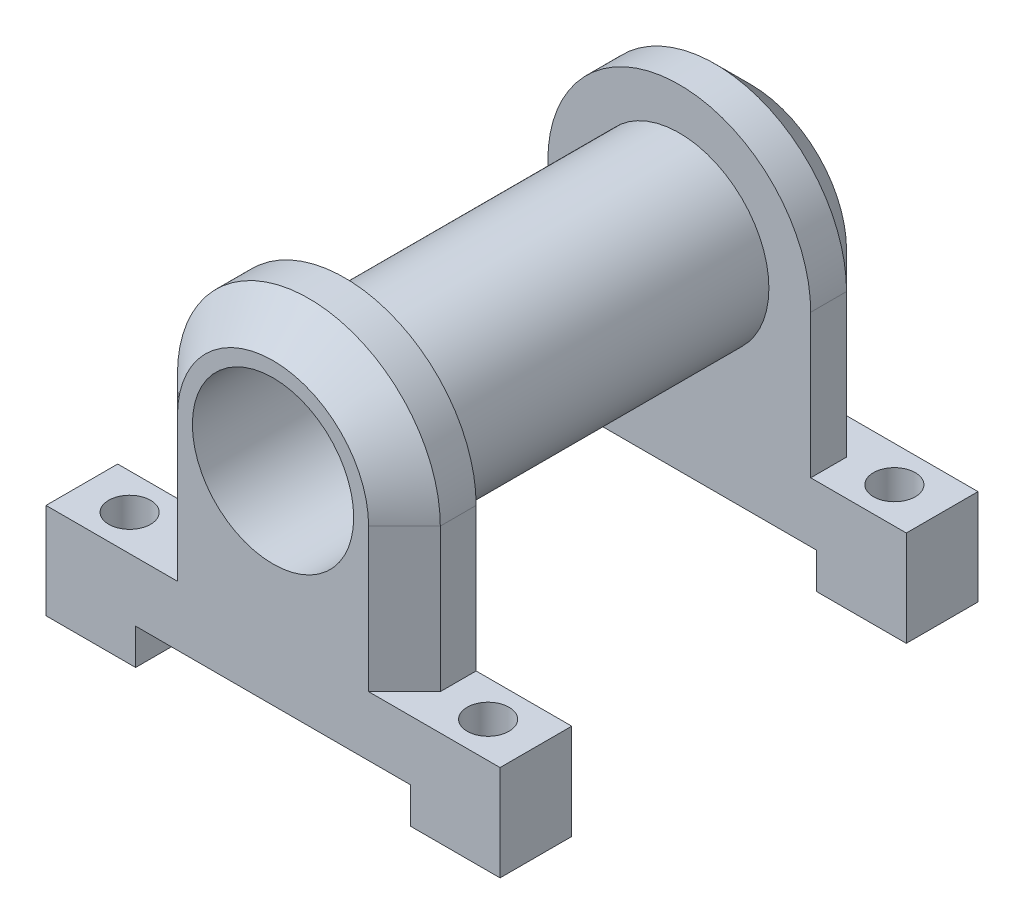
SolidWorks part; units mm, degrees
ref_plane "Front Plane" through (0, 0, 0) normal (0, 0, 1) x (1, 0, 0)
ref_plane "Top Plane" through (0, 0, 0) normal (0, 1, 0) x (1, 0, 0)
ref_plane "Right Plane" through (0, 0, 0) normal (1, 0, 0) x (0, 0, -1)
sketch "Sketch1" plane through (0, 0, 0) normal (0, 0, 1) x (1, 0, 0)
  line L0 (-11, 0) -> (-11, -12)
  line L1 (-11, -20) -> (11, -20)
  line L2 (11, -12) -> (11, 0)
  line L3 (-11, -12) -> (11, -12) construction
  line L4 (-11, -20) -> (-19, -20)
  line L6 (-11, -12) -> (-19, -12)
  line L7 (-19, -20) -> (-19, -12)
  line L8 (11, -20) -> (19, -20)
  line L10 (11, -12) -> (19, -12)
  line L11 (19, -20) -> (19, -12)
  arc A0 (11, 0) -> (-11, 0) centre (0, 0) ccw
  dimension "D1" = 22
  dimension "D2" = 20
  dimension "D3" = 8
  dimension "D4" = 8
extrude "Boss-Extrude1" add sketch "Sketch1" along normal blind 6
sketch "Sketch2" plane through (0, 0, 6) normal (0, 0, 1) x (1, 0, 0)
  circle A0 centre (0, 0) radius 7.5
  dimension "D1" = 15
extrude "Boss-Extrude2" add sketch "Sketch2" along normal blind 28
sketch "Sketch3" plane through (0, 0, 34) normal (0, 0, 1) x (1, 0, 0)
  line L3 (-11, 0) -> (-11, -12)
  line L4 (-19, -20) -> (19, -20)
  line L5 (11, -12) -> (11, 0)
  line L6 (-11, 0) -> (-11, -12)
  line L7 (-19, -20) -> (19, -20)
  line L8 (11, -12) -> (11, 0)
  line L13 (-19, -12) -> (-19, -20)
  line L14 (-19, -12) -> (-19, -20)
  line L15 (19, -20) -> (19, -12)
  line L16 (19, -20) -> (19, -12)
  line L17 (19, -12) -> (11, -12)
  line L18 (19, -12) -> (11, -12)
  line L19 (-11, -12) -> (-19, -12)
  line L20 (-11, -12) -> (-19, -12)
  arc A2 (11, 0) -> (-11, 0) centre (0, 0) ccw
  arc A3 (11, 0) -> (-11, 0) centre (0, 0) ccw
  dimension "D1" = 0
extrude "Boss-Extrude3" add sketch "Sketch3" along normal blind 6
sketch "Sketch4" plane through (0, 0, 40) normal (0, 0, 1) x (1, 0, 0)
  circle A0 centre (0, 0) radius 6.75
  dimension "D1" = 13.5
extrude "Cut-Extrude1" cut sketch "Sketch4" against normal through all
sketch "Sketch5" plane through (0, 0, 0) normal (0, 0, -1) x (-1, 0, 0)
  line L0 (19, -20) -> (-19, -20) construction
  line L1 (-11.5, -20) -> (11.5, -20)
  line L2 (-11.5, -20) -> (-11.5, -17)
  line L3 (-11.5, -17) -> (11.5, -17)
  line L4 (11.5, -20) -> (11.5, -17)
  line L5 (0, -17) -> (0, 0) construction
  dimension "D1" = 23
  dimension "D2" = 3
extrude "Cut-Extrude2" cut sketch "Sketch5" against normal through all and the other way through all
sketch "Sketch6" plane through (0, -12, 0) normal (0, 1, 0) x (1, 0, 0)
  line L0 (-15, -3) -> (15, -3) construction
  line L3 (0, -3) -> (0, 0) construction
  circle A0 centre (-15, -3) radius 1.75
  circle A1 centre (15, -3) radius 1.75
  circle A2 centre (15, -37) radius 1.75
  circle A3 centre (-15, -37) radius 1.75
  dimension "D3" = 3.5
  dimension "D1" = 30
  dimension "D2" = 3
  dimension "D4" = 2
extrude "Cut-Extrude3" cut sketch "Sketch6" against normal through all
chamfer "Chamfer1" distance 3 angle 45 6 edges at (11, -6, 40) (0, 11, 40) (-11, -6, 40) (11, -6, 0) (0, 11, 0) (-11, -6, 0)
